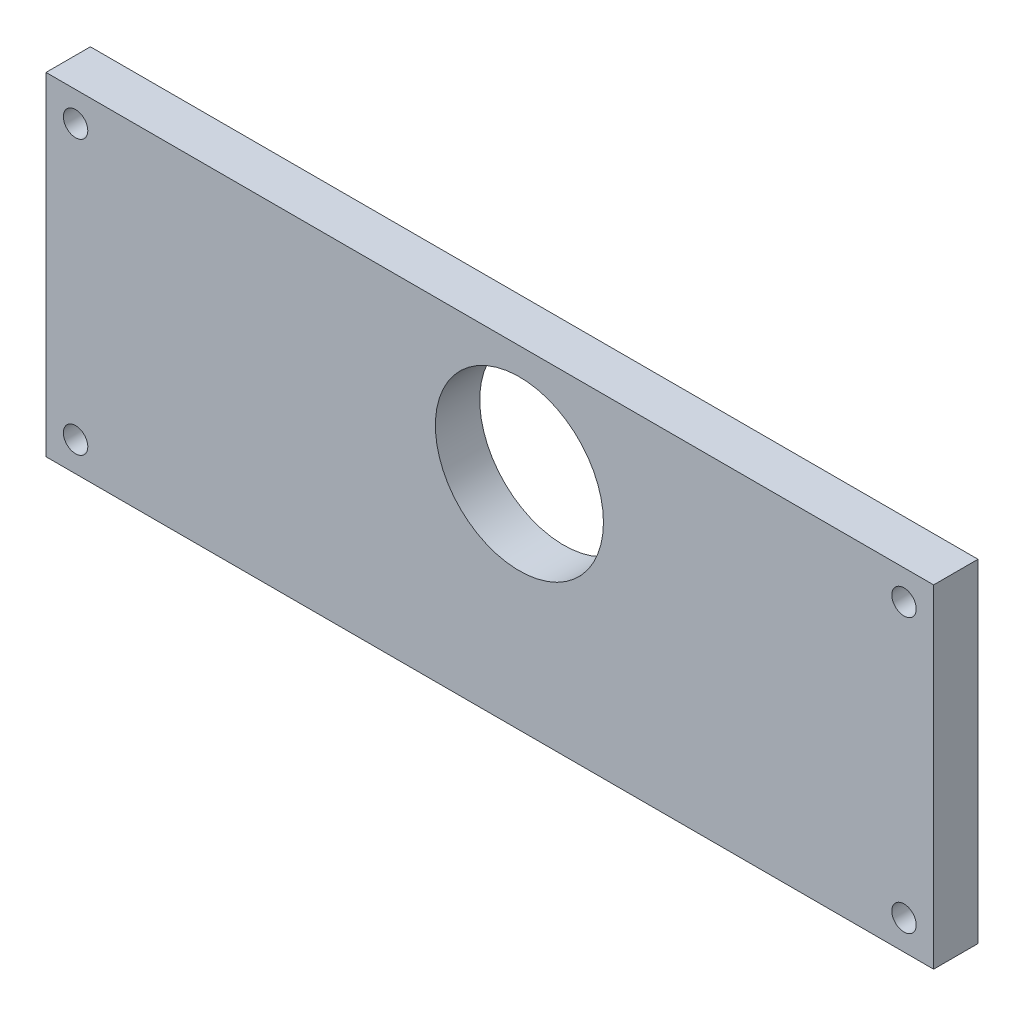
SolidWorks part; units mm, degrees
ref_plane "Front Plane" through (0, 0, 0) normal (0, 0, 1) x (1, 0, 0)
ref_plane "Top Plane" through (0, 0, 0) normal (0, 1, 0) x (1, 0, 0)
ref_plane "Right Plane" through (0, 0, 0) normal (1, 0, 0) x (0, 0, -1)
sketch "Sketch1" plane through (0, 0, 0) normal (0, 0, 1) x (1, 0, 0)
  line L0 (60, 45) -> (60, 0) construction
  line L1 (0, 0) -> (120, 0)
  line L2 (0, 0) -> (0, 45)
  line L3 (0, 45) -> (120, 45)
  line L4 (120, 0) -> (120, 45)
  line L5 (0, 22.5) -> (120, 22.5) construction
  line L6 (50.1436, 38) -> (64, 30) construction
  line L7 (64, 30) -> (42.232, 30) construction
  line L8 (64, 30) -> (64, 38.4979) construction
  circle A0 centre (64, 30) radius 11.3625
  circle A1 centre (4, 41) radius 1.65
  circle A2 centre (4, 4) radius 1.65
  circle A3 centre (116, 41) radius 1.65
  circle A4 centre (116, 4) radius 1.65
  circle A5 centre (50.1436, 38) radius 1.5 construction
  circle A6 centre (50.1436, 22) radius 1.5 construction
  circle A9 centre (77.8564, 22) radius 1.5 construction
  circle A10 centre (77.8564, 38) radius 1.5 construction
  dimension "D3" = 22.725
  dimension "D4" = 4
  dimension "D5" = 3.3
  dimension "D6" = 4
  dimension "D7" = 15
  dimension "D10" = 3
  dimension "D1" = 45
  dimension "D2" = 120
  dimension "D8" = 16
  dimension "D9" = 60
  dimension "D11" = 4
extrude "Boss-Extrude1" add sketch "Sketch1" along normal blind 6
sketch "Sketch2" plane through (0, 0, 6) normal (0, 0, 1) x (1, 0, 0)
  circle A0 centre (116, 4) radius 1.65 construction
  circle A1 centre (116, 41) radius 1.65 construction
  circle A2 centre (4, 4) radius 1.65 construction
  circle A3 centre (4, 41) radius 1.65 construction
  circle A4 centre (116, 4) radius 1.65
  circle A5 centre (116, 41) radius 1.65
  circle A6 centre (4, 4) radius 1.65
  circle A7 centre (4, 41) radius 1.65
  circle A8 centre (4, 41) radius 3
  circle A9 centre (4, 4) radius 3
  circle A10 centre (116, 4) radius 3
  circle A11 centre (116, 41) radius 3
  dimension "D1" = 1.35
extrude "Cut-Extrude1" cut sketch "Sketch2" along normal blind 3 from surface at -6 starting at face at (114.35, 41, 0)
